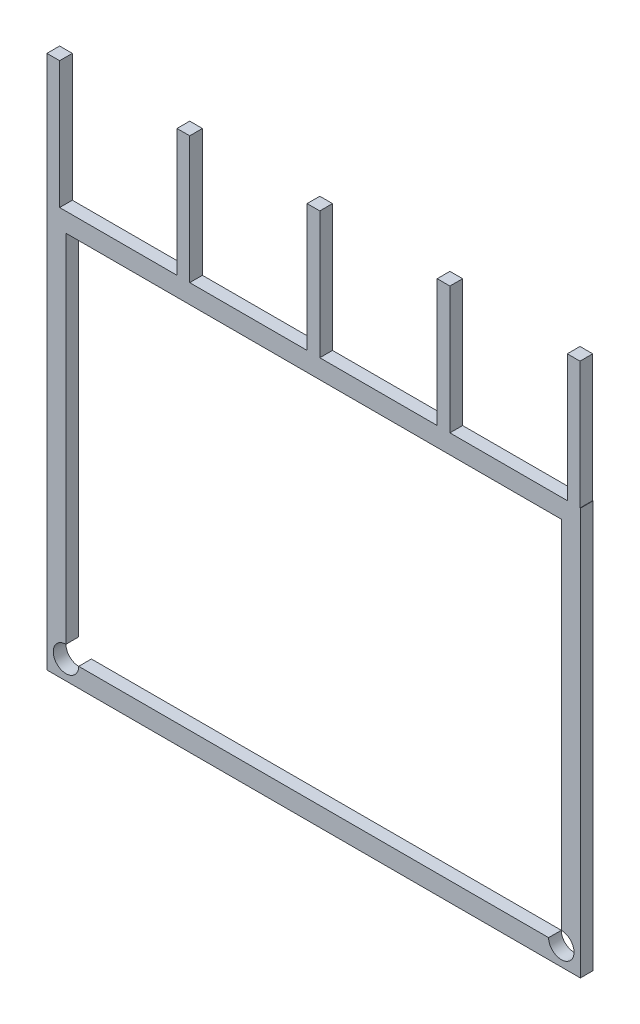
SolidWorks part; units mm, degrees
ref_plane "Front Plane" through (0, 0, 0) normal (0, 0, 1) x (1, 0, 0)
ref_plane "Top Plane" through (0, 0, 0) normal (0, 1, 0) x (1, 0, 0)
ref_plane "Right Plane" through (0, 0, 0) normal (1, 0, 0) x (0, 0, -1)
sketch "Sketch1" plane through (0, 0, 0) normal (0, 0, 1) x (1, 0, 0)
  line L0 (-20.975, -15.9965) -> (-20.975, 15.9965)
  line L1 (19.475, -14.4965) -> (-19.475, -14.4965)
  line L2 (19.475, -14.4965) -> (19.475, 14.4965)
  line L3 (19.475, 14.4965) -> (-19.475, 14.4965)
  line L4 (-19.475, -14.4965) -> (-19.475, 14.4965)
  line L5 (0, 14.4965) -> (0, -14.4965) construction
  line L6 (19.475, 0) -> (-19.475, 0) construction
  line L7 (20.975, 15.9965) -> (-20.975, 15.9965)
  line L8 (20.975, -15.9965) -> (20.975, 15.9965)
  line L9 (20.975, -15.9965) -> (-20.975, -15.9965)
  circle A0 centre (-19.475, -14.4965) radius 1
  circle A1 centre (19.475, -14.4965) radius 1
  point P0 (0, 0)
  dimension "D3" = 2
  dimension "D4" = 2
  dimension "D1" = 38.95
  dimension "D2" = 28.993
  dimension "D5" = 1.5
extrude "Boss-Extrude1" add sketch "Sketch1" along normal mid plane 1 contours L9 L8 L7 L0 A1 L1 A0 L4 L3 L2
sketch "Sketch2" plane through (0, 15.9965, 0) normal (0, 1, 0) x (1, 0, 0)
  line L1 (-19.975, 0.5) -> (-20.975, 0.5)
  line L2 (-19.975, 0.5) -> (-19.975, -0.5)
  line L3 (-19.975, -0.5) -> (-20.975, -0.5)
  line L4 (-20.975, 0.5) -> (-20.975, -0.5)
  line L5 (-20.475, -0.5) -> (-20.475, 0.5) construction
  line L6 (-19.975, 0) -> (-20.975, 0) construction
  point P0 (-20.475, 0)
  dimension "D1" = 1
  dimension "D2" = 1
extrude "Boss-Extrude2" add sketch "Sketch2" along normal blind 10
pattern_linear "LPattern1" count 5 spacing 10.23 along (1, 0, 0) of "Boss-Extrude2"
